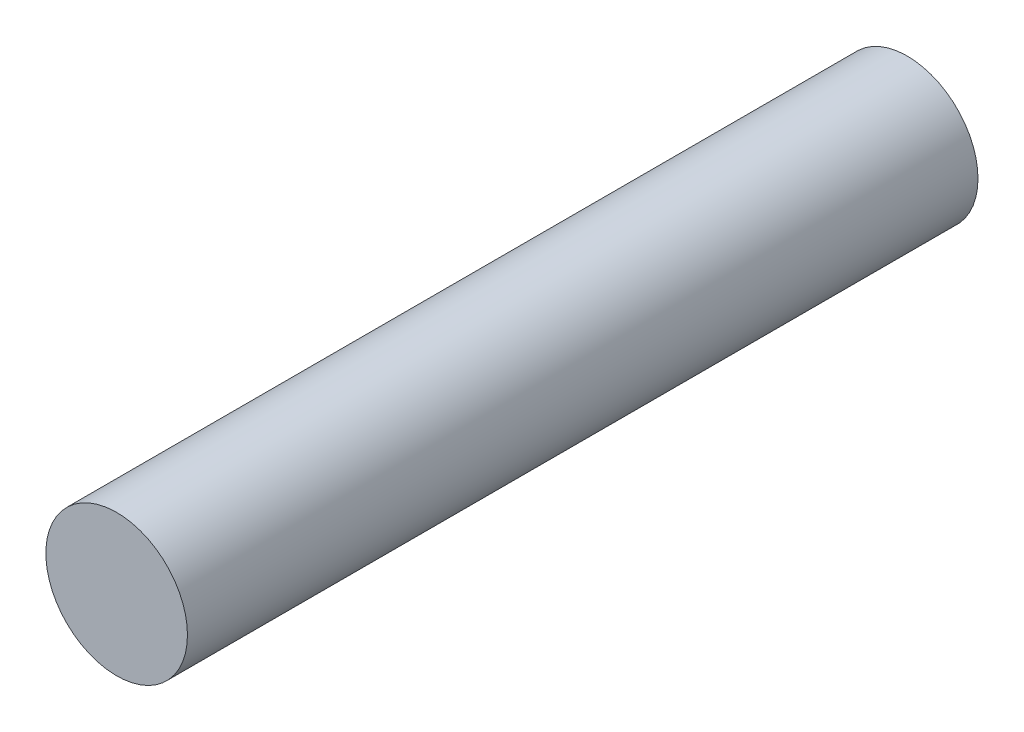
SolidWorks part; units mm, degrees
ref_plane "Front Plane" through (0, 0, 0) normal (0, 0, 1) x (1, 0, 0)
ref_plane "Top Plane" through (0, 0, 0) normal (0, 1, 0) x (1, 0, 0)
ref_plane "Right Plane" through (0, 0, 0) normal (1, 0, 0) x (0, 0, -1)
sketch "Main Body Sketch" plane through (0, 0, 0) normal (0, 0, 1) x (1, 0, 0)
  circle A0 centre (0, 0) radius 1.5
  dimension "D1" = 3
extrude "Main Body Extrude" add sketch "Main Body Sketch" against normal blind 16.75
